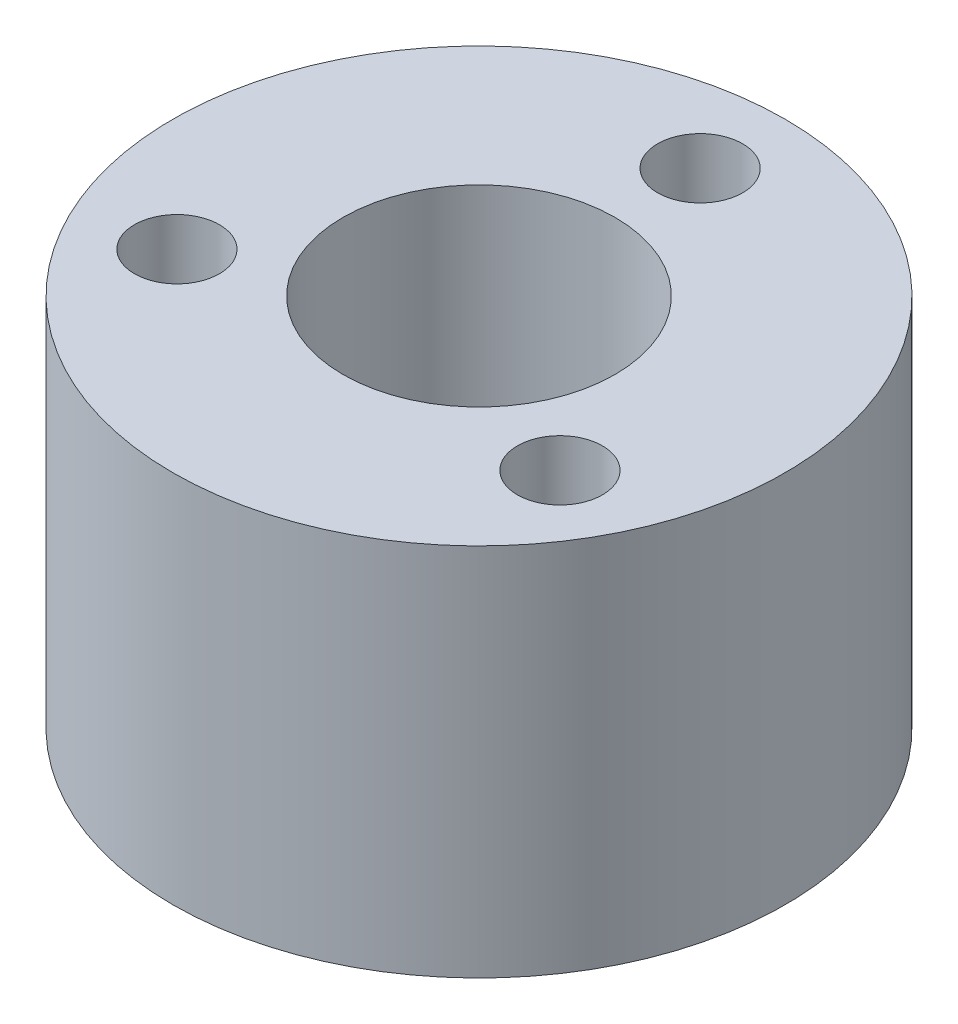
SolidWorks part; units mm, degrees
ref_plane "前视基准面" through (0, 0, 0) normal (0, 0, 1) x (1, 0, 0)
ref_plane "上视基准面" through (0, 0, 0) normal (0, 1, 0) x (1, 0, 0)
ref_plane "右视基准面" through (0, 0, 0) normal (1, 0, 0) x (0, 0, -1)
sketch "草图1" plane through (0, 0, 0) normal (0, 1, 0) x (1, 0, 0)
  line L0 (0, 6.5) -> (0, 4) construction
  circle A0 centre (0, 0) radius 9
  circle A1 centre (0, 0) radius 4
  circle A2 centre (0, 6.5) radius 1.25
  circle A3 centre (5.6292, -3.25) radius 1.25
  circle A4 centre (-5.6292, -3.25) radius 1.25
  point P14 (0, 0)
  dimension "D1" = 18
  dimension "D2" = 8
  dimension "D3" = 2.5
  dimension "D4" = 2.5
  dimension "D5" = 3
extrude "凸台-拉伸1" add sketch "草图1" along normal blind 11
